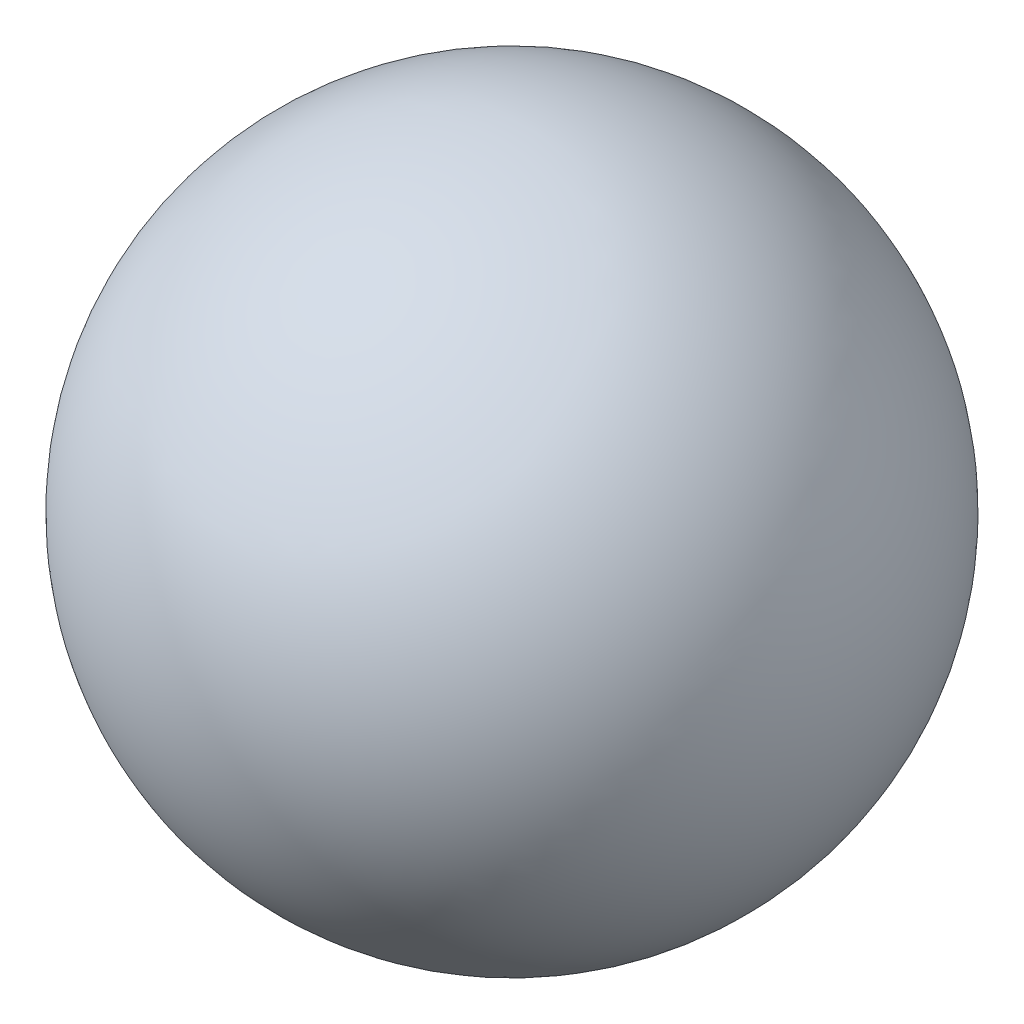
SolidWorks part; units mm, degrees
material "ABS"
ref_plane "前视基准面" through (0, 0, 0) normal (0, 0, 1) x (1, 0, 0)
ref_plane "上视基准面" through (0, 0, 0) normal (0, 1, 0) x (1, 0, 0)
ref_plane "右视基准面" through (0, 0, 0) normal (1, 0, 0) x (0, 0, -1)
sketch "草图1" plane through (0, 0, 0) normal (0, 1, 0) x (1, 0, 0)
  line L0 (0, 8.5) -> (0, -8.5)
  arc A0 (0, 8.5) -> (0, -8.5) centre (0, 0) ccw
  dimension "D1" = 8.5
revolve "旋转1" add sketch "草图1" angle 360 about L0
